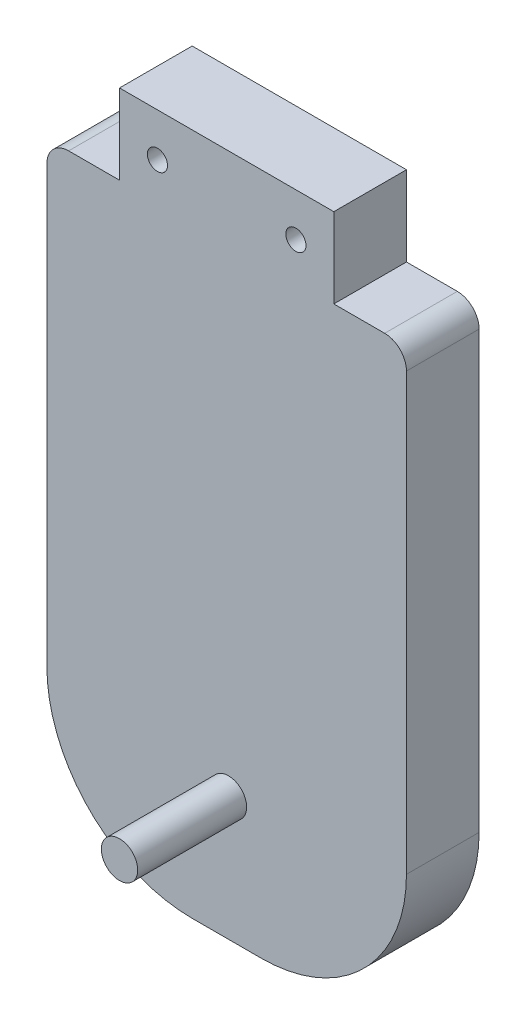
SolidWorks part; units mm, degrees
ref_plane "Ön Düzlem" through (0, 0, 0) normal (0, 0, 1) x (1, 0, 0)
ref_plane "Üst Düzlem" through (0, 0, 0) normal (0, 1, 0) x (1, 0, 0)
ref_plane "Sağ Düzlem" through (0, 0, 0) normal (1, 0, 0) x (0, 0, -1)
ref_plane "Düzlem1" through (0, 0, 10) normal (0, 0, 1) x (1, 0, 0)
sketch "Çizim1" plane through (0, 0, 10) normal (0, 0, 1) x (1, 0, 0)
  line L0 (11.5757, 67.1812) -> (4.5757, 67.1812)
  line L1 (1.5757, 64.1812) -> (1.5757, 4.1812)
  line L4 (21.5757, -15.8188) -> (31.0757, -15.8188)
  line L7 (51.0757, 4.1812) -> (51.0757, 64.1812)
  line L8 (48.0757, 67.1812) -> (41.0757, 67.1812)
  line L9 (41.0757, 67.1812) -> (41.0757, 78.1812)
  line L10 (41.0757, 78.1812) -> (11.5757, 78.1812)
  line L11 (11.5757, 78.1812) -> (11.5757, 67.1812)
  arc A0 (4.5757, 67.1812) -> (1.5757, 64.1812) centre (4.5757, 64.1812) ccw
  arc A7 (51.0757, 64.1812) -> (48.0757, 67.1812) centre (48.0757, 64.1812) ccw
  arc A8 (31.0757, -15.8188) -> (51.0757, 4.1812) centre (31.0757, 4.1812) ccw
  arc A9 (1.5757, 4.1812) -> (21.5757, -15.8188) centre (21.5757, 4.1812) ccw
  circle A12 centre (16.7957, 72.2222) radius 1.3889
  circle A13 centre (35.8535, 72.2222) radius 1.3889
  dimension "D1" = 5.2222
  dimension "D7" = 20
  dimension "D8" = 60
  dimension "D9" = 3
  dimension "D10" = 3
  dimension "D2" = 5.22
  dimension "D3" = 7
  dimension "D4" = 29.5
  dimension "D5" = 7
  dimension "D6" = 11
extrude "Yükseklik-Ekstrüzyon1" add sketch "Çizim1" against normal blind 10
sketch "Çizim2" plane through (0, 0, 10) normal (0, 0, 1) x (1, 0, 0)
  circle A0 centre (26.5757, 1.1812) radius 2.5
extrude "Yükseklik-Ekstrüzyon2" add sketch "Çizim2" along normal blind 15 contours A0
